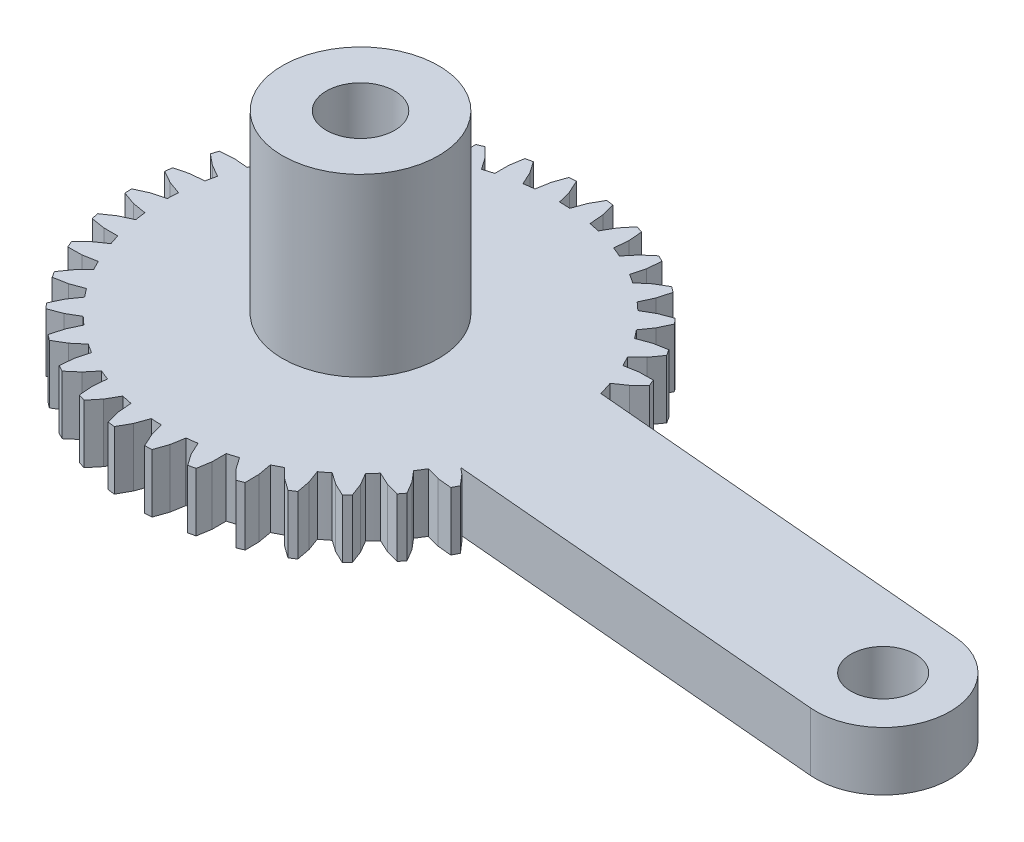
SolidWorks part; units mm, degrees
ref_plane "前视基准面" through (0, 0, 0) normal (0, 0, 1) x (1, 0, 0)
ref_plane "上视基准面" through (0, 0, 0) normal (0, 1, 0) x (1, 0, 0)
ref_plane "右视基准面" through (0, 0, 0) normal (1, 0, 0) x (0, 0, -1)
other "Configuration Table"
sketch "草图1" plane through (0, 0, 0) normal (0, 1, 0) x (1, 0, 0)
  line L0 (4.0827, 9.1823) -> (4.5422, 9.734)
  line L2 (4.5422, 9.734) -> (5.0868, 10.2019)
  line L3 (5.0868, 10.2019) -> (5.4091, 10.0347)
  line L4 (5.248, 10.1183) -> (4.4599, 8.5989) construction
  line L5 (5.3403, 9.32) -> (5.4091, 10.0347)
  line L6 (5.1541, 8.6266) -> (5.3403, 9.32)
  line L7 (5.6151, 8.3338) -> (6.1635, 8.7973)
  line L8 (6.1635, 8.7973) -> (6.781, 9.1636)
  line L9 (6.781, 9.1636) -> (7.0695, 8.9429)
  line L10 (6.8776, 8.2511) -> (7.0695, 8.9429)
  line L11 (6.5738, 7.6005) -> (6.8776, 8.2511)
  line L12 (6.977, 7.2322) -> (7.5975, 7.5934)
  line L13 (7.5975, 7.5934) -> (8.2693, 7.8469)
  line L14 (8.2693, 7.8469) -> (8.515, 7.5795)
  line L15 (8.2059, 6.9314) -> (8.515, 7.5795)
  line L16 (7.7937, 6.3435) -> (8.2059, 6.9314)
  line L17 (8.1268, 5.9108) -> (8.8006, 6.1588)
  line L18 (8.8006, 6.1588) -> (9.5062, 6.2917)
  line L19 (9.5062, 6.2917) -> (9.7018, 5.9857)
  line L20 (9.2849, 5.4012) -> (9.7018, 5.9857)
  line L21 (8.7769, 4.8938) -> (9.2849, 5.4012)
  line L22 (9.0298, 4.4098) -> (9.7364, 4.537)
  line L23 (9.7364, 4.537) -> (10.4543, 4.5454)
  line L24 (10.4543, 4.5454) -> (10.5938, 4.2101)
  line L25 (10.0817, 3.7068) -> (10.5938, 4.2101)
  line L26 (9.4933, 3.2953) -> (10.0817, 3.7068)
  line L47 (9.4047, -4.268) -> (9.734, -4.5422)
  line L48 (9.734, -4.5422) -> (10.2019, -5.0868)
  line L49 (10.2019, -5.0868) -> (10.0347, -5.4091)
  line L50 (9.32, -5.3403) -> (10.0347, -5.4091)
  line L51 (8.6266, -5.1541) -> (9.32, -5.3403)
  line L52 (8.3338, -5.6151) -> (8.7973, -6.1635)
  line L53 (8.7973, -6.1635) -> (9.1636, -6.781)
  line L54 (9.1636, -6.781) -> (8.9429, -7.0695)
  line L55 (8.2511, -6.8776) -> (8.9429, -7.0695)
  line L56 (7.6005, -6.5738) -> (8.2511, -6.8776)
  line L57 (7.2322, -6.977) -> (7.5934, -7.5975)
  line L58 (7.5934, -7.5975) -> (7.8469, -8.2693)
  line L59 (7.8469, -8.2693) -> (7.5795, -8.515)
  line L60 (6.9314, -8.2059) -> (7.5795, -8.515)
  line L61 (6.3435, -7.7937) -> (6.9314, -8.2059)
  line L62 (5.9108, -8.1268) -> (6.1588, -8.8006)
  line L63 (6.1588, -8.8006) -> (6.2917, -9.5062)
  line L64 (6.2917, -9.5062) -> (5.9857, -9.7018)
  line L65 (5.4012, -9.2849) -> (5.9857, -9.7018)
  line L66 (4.8938, -8.7769) -> (5.4012, -9.2849)
  line L67 (4.4098, -9.0298) -> (4.537, -9.7364)
  line L68 (4.537, -9.7364) -> (4.5454, -10.4543)
  line L69 (4.5454, -10.4543) -> (4.2101, -10.5938)
  line L70 (3.7068, -10.0817) -> (4.2101, -10.5938)
  line L71 (3.2953, -9.4933) -> (3.7068, -10.0817)
  line L72 (2.7748, -9.6583) -> (2.7773, -10.3763)
  line L73 (2.7773, -10.3763) -> (2.6609, -11.0848)
  line L74 (2.6609, -11.0848) -> (2.3065, -11.1639)
  line L75 (1.8998, -10.5722) -> (2.3065, -11.1639)
  line L76 (1.5968, -9.9213) -> (1.8998, -10.5722)
  line L77 (1.0555, -9.9934) -> (0.9333, -10.701)
  line L78 (0.9333, -10.701) -> (0.6957, -11.3785)
  line L79 (0.6957, -11.3785) -> (0.3329, -11.3949)
  line L80 (0.0351, -10.7415) -> (0.3329, -11.3949)
  line L81 (-0.1503, -10.0479) -> (0.0351, -10.7415)
  line L82 (-0.6959, -10.0249) -> (-0.9391, -10.7005)
  line L83 (-0.9391, -10.7005) -> (-1.2908, -11.3264)
  line L84 (-1.2908, -11.3264) -> (-1.6509, -11.2796)
  line L85 (-1.8307, -10.5844) -> (-1.6509, -11.2796)
  line L86 (-1.8928, -9.8691) -> (-1.8307, -10.5844)
  line L87 (-2.4261, -9.7517) -> (-2.7829, -10.3748)
  line L88 (-2.7829, -10.3748) -> (-3.238, -10.9302)
  line L89 (-3.238, -10.9302) -> (-3.5845, -10.8215)
  line L90 (-3.6408, -10.1057) -> (-3.5845, -10.8215)
  line L91 (-3.5778, -9.3905) -> (-3.6408, -10.1057)
  line L92 (-4.0827, -9.1823) -> (-4.5422, -9.734)
  line L93 (-4.5422, -9.734) -> (-5.0868, -10.2019)
  line L94 (-5.0868, -10.2019) -> (-5.4091, -10.0347)
  line L95 (-5.3403, -9.32) -> (-5.4091, -10.0347)
  line L96 (-5.1541, -8.6266) -> (-5.3403, -9.32)
  line L97 (-5.6151, -8.3338) -> (-6.1635, -8.7973)
  line L98 (-6.1635, -8.7973) -> (-6.781, -9.1636)
  line L99 (-6.781, -9.1636) -> (-7.0695, -8.9429)
  line L100 (-6.8776, -8.2511) -> (-7.0695, -8.9429)
  line L101 (-6.5738, -7.6005) -> (-6.8776, -8.2511)
  line L102 (-6.977, -7.2322) -> (-7.5975, -7.5934)
  line L103 (-7.5975, -7.5934) -> (-8.2693, -7.8469)
  line L104 (-8.2693, -7.8469) -> (-8.515, -7.5795)
  line L105 (-8.2059, -6.9314) -> (-8.515, -7.5795)
  line L106 (-7.7937, -6.3435) -> (-8.2059, -6.9314)
  line L107 (-8.1268, -5.9108) -> (-8.8006, -6.1588)
  line L108 (-8.8006, -6.1588) -> (-9.5062, -6.2917)
  line L109 (-9.5062, -6.2917) -> (-9.7018, -5.9857)
  line L110 (-9.2849, -5.4012) -> (-9.7018, -5.9857)
  line L111 (-8.7769, -4.8938) -> (-9.2849, -5.4012)
  line L112 (-9.0298, -4.4098) -> (-9.7364, -4.537)
  line L113 (-9.7364, -4.537) -> (-10.4543, -4.5454)
  line L114 (-10.4543, -4.5454) -> (-10.5938, -4.2101)
  line L115 (-10.0817, -3.7068) -> (-10.5938, -4.2101)
  line L116 (-9.4933, -3.2953) -> (-10.0817, -3.7068)
  line L117 (-9.6583, -2.7748) -> (-10.3763, -2.7773)
  line L118 (-10.3763, -2.7773) -> (-11.0848, -2.6609)
  line L119 (-11.0848, -2.6609) -> (-11.1639, -2.3065)
  line L120 (-10.5722, -1.8998) -> (-11.1639, -2.3065)
  line L121 (-9.9213, -1.5968) -> (-10.5722, -1.8998)
  line L122 (-9.9934, -1.0555) -> (-10.701, -0.9333)
  line L123 (-10.701, -0.9333) -> (-11.3785, -0.6957)
  line L124 (-11.3785, -0.6957) -> (-11.3949, -0.3329)
  line L125 (-10.7415, -0.0351) -> (-11.3949, -0.3329)
  line L126 (-10.0479, 0.1503) -> (-10.7415, -0.0351)
  line L127 (-10.0249, 0.6959) -> (-10.7005, 0.9391)
  line L128 (-10.7005, 0.9391) -> (-11.3264, 1.2908)
  line L129 (-11.3264, 1.2908) -> (-11.2796, 1.6509)
  line L130 (-10.5844, 1.8307) -> (-11.2796, 1.6509)
  line L131 (-9.8691, 1.8928) -> (-10.5844, 1.8307)
  line L132 (-9.7517, 2.4261) -> (-10.3748, 2.7829)
  line L133 (-10.3748, 2.7829) -> (-10.9302, 3.238)
  line L134 (-10.9302, 3.238) -> (-10.8215, 3.5845)
  line L135 (-10.1057, 3.6408) -> (-10.8215, 3.5845)
  line L136 (-9.3905, 3.5778) -> (-10.1057, 3.6408)
  line L137 (-9.1823, 4.0827) -> (-9.734, 4.5422)
  line L138 (-9.734, 4.5422) -> (-10.2019, 5.0868)
  line L139 (-10.2019, 5.0868) -> (-10.0347, 5.4091)
  line L140 (-9.32, 5.3403) -> (-10.0347, 5.4091)
  line L141 (-8.6266, 5.1541) -> (-9.32, 5.3403)
  line L142 (-8.3338, 5.6151) -> (-8.7973, 6.1635)
  line L143 (-8.7973, 6.1635) -> (-9.1636, 6.781)
  line L144 (-9.1636, 6.781) -> (-8.9429, 7.0695)
  line L145 (-8.2511, 6.8776) -> (-8.9429, 7.0695)
  line L146 (-7.6005, 6.5738) -> (-8.2511, 6.8776)
  line L147 (-7.2322, 6.977) -> (-7.5934, 7.5975)
  line L148 (-7.5934, 7.5975) -> (-7.8469, 8.2693)
  line L149 (-7.8469, 8.2693) -> (-7.5795, 8.515)
  line L150 (-6.9314, 8.2059) -> (-7.5795, 8.515)
  line L151 (-6.3435, 7.7937) -> (-6.9314, 8.2059)
  line L152 (-5.9108, 8.1268) -> (-6.1588, 8.8006)
  line L153 (-6.1588, 8.8006) -> (-6.2917, 9.5062)
  line L154 (-6.2917, 9.5062) -> (-5.9857, 9.7018)
  line L155 (-5.4012, 9.2849) -> (-5.9857, 9.7018)
  line L156 (-4.8938, 8.7769) -> (-5.4012, 9.2849)
  line L157 (-4.4098, 9.0298) -> (-4.537, 9.7364)
  line L158 (-4.537, 9.7364) -> (-4.5454, 10.4543)
  line L159 (-4.5454, 10.4543) -> (-4.2101, 10.5938)
  line L160 (-3.7068, 10.0817) -> (-4.2101, 10.5938)
  line L161 (-3.2953, 9.4933) -> (-3.7068, 10.0817)
  line L162 (-2.7748, 9.6583) -> (-2.7773, 10.3763)
  line L163 (-2.7773, 10.3763) -> (-2.6609, 11.0848)
  line L164 (-2.6609, 11.0848) -> (-2.3065, 11.1639)
  line L165 (-1.8998, 10.5722) -> (-2.3065, 11.1639)
  line L166 (-1.5968, 9.9213) -> (-1.8998, 10.5722)
  line L167 (-1.0555, 9.9934) -> (-0.9333, 10.701)
  line L168 (-0.9333, 10.701) -> (-0.6957, 11.3785)
  line L169 (-0.6957, 11.3785) -> (-0.3329, 11.3949)
  line L170 (-0.0351, 10.7415) -> (-0.3329, 11.3949)
  line L171 (0.1503, 10.0479) -> (-0.0351, 10.7415)
  line L172 (0.6959, 10.0249) -> (0.9391, 10.7005)
  line L173 (0.9391, 10.7005) -> (1.2908, 11.3264)
  line L174 (1.2908, 11.3264) -> (1.6509, 11.2796)
  line L175 (1.8307, 10.5844) -> (1.6509, 11.2796)
  line L176 (1.8928, 9.8691) -> (1.8307, 10.5844)
  line L177 (2.4261, 9.7517) -> (2.7829, 10.3748)
  line L178 (2.7829, 10.3748) -> (3.238, 10.9302)
  line L179 (3.238, 10.9302) -> (3.5845, 10.8215)
  line L180 (3.6408, 10.1057) -> (3.5845, 10.8215)
  line L181 (3.5778, 9.3905) -> (3.6408, 10.1057)
  line L182 (5.1731, 8.6974) -> (5.2626, 8.6577) construction
  line L183 (0, 0) -> (9.1823, -4.0827) construction
  line L189 (9.6583, 2.7748) -> (10.3763, 2.7773) [skipped]
  line L190 (10.3763, 2.7773) -> (11.0848, 2.6609) [skipped]
  line L191 (11.0848, 2.6609) -> (11.1639, 2.3065) [skipped]
  line L192 (10.5722, 1.8998) -> (11.1639, 2.3065) [skipped]
  line L193 (9.9213, 1.5968) -> (10.5722, 1.8998) [skipped]
  line L194 (9.9934, 1.0555) -> (10.701, 0.9333) [skipped]
  line L195 (10.701, 0.9333) -> (11.3785, 0.6957) [skipped]
  line L196 (11.3785, 0.6957) -> (11.3949, 0.3329) [skipped]
  line L197 (10.7415, 0.0351) -> (11.3949, 0.3329) [skipped]
  line L198 (10.0479, -0.1503) -> (10.7415, 0.0351) [skipped]
  line L199 (9.7517, -2.4261) -> (10.3748, -2.7829) [skipped]
  line L200 (10.3748, -2.7829) -> (10.9302, -3.238) [skipped]
  line L201 (10.9302, -3.238) -> (10.8215, -3.5845) [skipped]
  line L202 (10.1057, -3.6408) -> (10.8215, -3.5845) [skipped]
  line L203 (9.3905, -3.5778) -> (10.1057, -3.6408) [skipped]
  line L204 (10.5844, -1.8307) -> (11.2796, -1.6509) [skipped]
  line L205 (11.3264, -1.2908) -> (11.2796, -1.6509) [skipped]
  line L206 (10.7005, -0.9391) -> (11.3264, -1.2908) [skipped]
  line L207 (10.0249, -0.6959) -> (10.7005, -0.9391) [skipped]
  line L208 (9.8691, -1.8928) -> (10.5844, -1.8307) [skipped]
  line L209 (0, 0) -> (29.3723, -2.039) construction
  line L210 (9.1823, -4.0827) -> (29.1343, -5.4677) construction
  line L212 (0, 0) -> (9.7053, 2.6058) construction
  line L214 (9.1096, -4.2423) -> (0, 0) construction
  line L215 (9.4047, -4.268) -> (29.0344, -5.9753)
  line L216 (0, 0) -> (29.3322, -2.5513) construction
  line L217 (9.7053, 2.6058) -> (29.63, 0.8727)
  line L218 (9.7053, 2.6058) -> (0, 0) construction
  line L219 (29.0344, -5.9753) -> (29.63, 0.8727) construction
  arc A0 (-5.9108, 8.1268) -> (-6.3435, 7.7937) centre (0, 0) ccw
  arc A1 (-4.4098, 9.0298) -> (-4.8938, 8.7769) centre (0, 0) ccw
  arc A2 (-2.7748, 9.6583) -> (-3.2953, 9.4933) centre (0, 0) ccw
  arc A3 (-1.0555, 9.9934) -> (-1.5968, 9.9213) centre (0, 0) ccw
  arc A4 (-7.2322, 6.977) -> (-7.6005, 6.5738) centre (0, 0) ccw
  arc A5 (-8.3338, 5.6151) -> (-8.6266, 5.1541) centre (0, 0) ccw
  arc A6 (-9.1823, 4.0827) -> (-9.3905, 3.5778) centre (0, 0) ccw
  arc A7 (-9.7517, 2.4261) -> (-9.8691, 1.8928) centre (0, 0) ccw
  arc A8 (-10.0249, 0.6959) -> (-10.0479, 0.1503) centre (0, 0) ccw
  arc A9 (-9.9934, -1.0555) -> (-9.9213, -1.5968) centre (0, 0) ccw
  arc A10 (-9.6583, -2.7748) -> (-9.4933, -3.2953) centre (0, 0) ccw
  arc A11 (-9.0298, -4.4098) -> (-8.7769, -4.8938) centre (0, 0) ccw
  arc A12 (-8.1268, -5.9108) -> (-7.7937, -6.3435) centre (0, 0) ccw
  arc A13 (-6.977, -7.2322) -> (-6.5738, -7.6005) centre (0, 0) ccw
  arc A14 (-5.6151, -8.3338) -> (-5.1541, -8.6266) centre (0, 0) ccw
  arc A15 (-4.0827, -9.1823) -> (-3.5778, -9.3905) centre (0, 0) ccw
  arc A16 (-2.4261, -9.7517) -> (-1.8928, -9.8691) centre (0, 0) ccw
  arc A17 (-0.6959, -10.0249) -> (-0.1503, -10.0479) centre (0, 0) ccw
  arc A18 (1.0555, -9.9934) -> (1.5968, -9.9213) centre (0, 0) ccw
  arc A19 (2.7748, -9.6583) -> (3.2953, -9.4933) centre (0, 0) ccw
  arc A20 (4.4098, -9.0298) -> (4.8938, -8.7769) centre (0, 0) ccw
  arc A21 (5.9108, -8.1268) -> (6.3435, -7.7937) centre (0, 0) ccw
  arc A22 (7.2322, -6.977) -> (7.6005, -6.5738) centre (0, 0) ccw
  arc A23 (8.3338, -5.6151) -> (8.6266, -5.1541) centre (0, 0) ccw
  arc A28 (0.6959, 10.0249) -> (0.1503, 10.0479) centre (0, 0) ccw
  arc A29 (2.4261, 9.7517) -> (1.8928, 9.8691) centre (0, 0) ccw
  arc A30 (4.0827, 9.1823) -> (3.5778, 9.3905) centre (0, 0) ccw
  arc A31 (5.6151, 8.3338) -> (5.1541, 8.6266) centre (0, 0) ccw
  arc A32 (6.977, 7.2322) -> (6.5738, 7.6005) centre (0, 0) ccw
  arc A33 (8.1268, 5.9108) -> (7.7937, 6.3435) centre (0, 0) ccw
  arc A34 (9.0298, 4.4098) -> (8.7769, 4.8938) centre (0, 0) ccw
  arc A35 (9.7053, 2.6058) -> (9.4933, 3.2953) centre (0, 0) ccw
  circle A38 centre (0, 0) radius 1.75
  circle A39 centre (0, 0) radius 7 construction
  circle A40 centre (0, 7) radius 1 construction
  circle A41 centre (7, 0) radius 1 construction
  circle A42 centre (0, -7) radius 1 construction
  circle A43 centre (-7, 0) radius 1 construction
  arc A44 (29.1343, -5.4677) -> (29.6103, 1.3897) centre (29.3723, -2.039) ccw construction
  circle A46 centre (0, 0) radius 10.049 construction
  arc A48 (29.0344, -5.9753) -> (29.63, 0.8727) centre (29.3322, -2.5513) ccw
  circle A49 centre (29.3322, -2.5513) radius 1.65
  point P51 (0, 0)
  point P224 (0, 0)
  dimension "D1" = 20.098
  dimension "D10" = 1
  dimension "D11" = 3.5
  dimension "D12" = 2
  dimension "D14" = 14
  dimension "D9" = 3.3
  dimension "D2" = 0.718
  dimension "D3" = 20
  dimension "D4" = 170.464
  dimension "D5" = 0.718
  dimension "D6" = 111.916
  dimension "D7" = 36
  dimension "D8" = 20
  dimension "D15" = 20
  dimension "D16" = 20
  dimension "D13" = 4
extrude "凸台-拉伸1" add sketch "草图1" along normal blind 3
sketch "草图2" plane through (0, 3, 0) normal (0, 1, 0) x (1, 0, 0)
  circle A0 centre (0, 0) radius 10.7416 construction
sketch "草图3" plane through (0, 3, 0) normal (0, 1, 0) x (1, 0, 0)
  circle A0 centre (0, 0) radius 1.75
  circle A1 centre (0, 0) radius 4
  dimension "D1" = 8
  dimension "D2" = 3.5
extrude "凸台-拉伸2" add sketch "草图3" along normal blind 9
